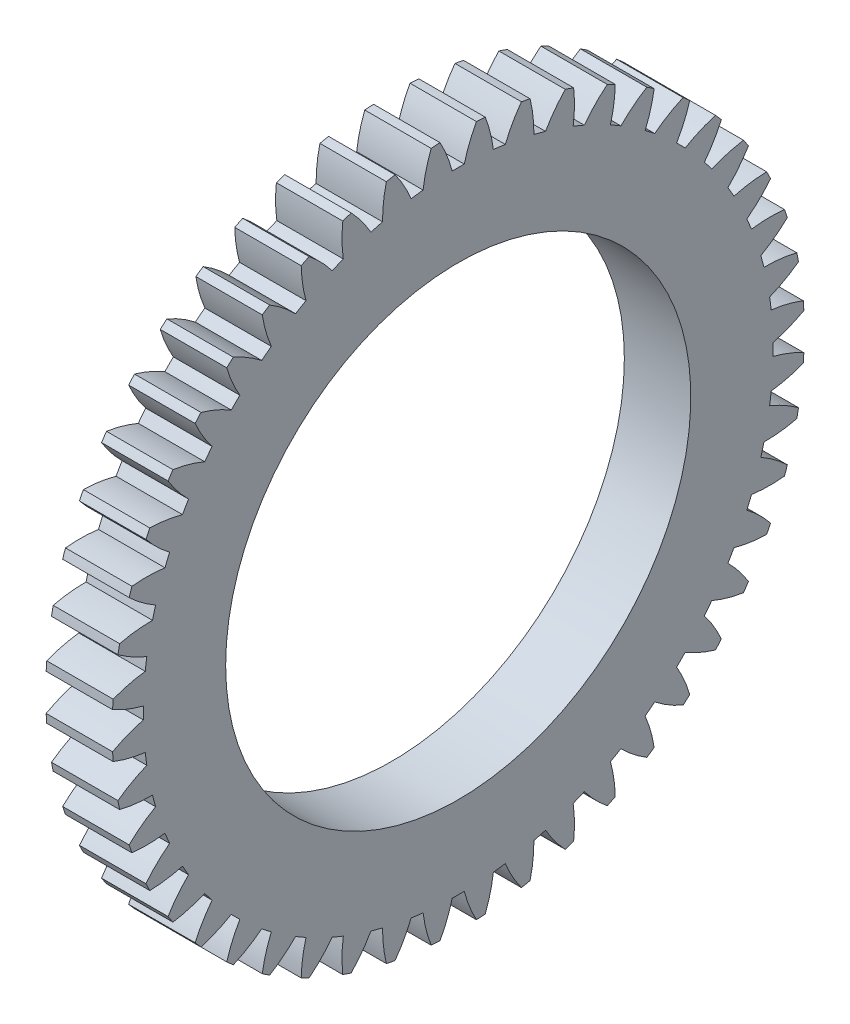
SolidWorks part; units mm, degrees
ref_plane "Plane1" through (0, 0, 0) normal (0, 0, 1) x (1, 0, 0)
ref_plane "Plane2" through (0, 0, 0) normal (0, 1, 0) x (1, 0, 0)
ref_plane "Plane3" through (0, 0, 0) normal (1, 0, 0) x (0, 0, -1)
other "Configuration Table"
sketch "HoldingSke" plane through (0, 0, 0) normal (0, 1, 0) x (1, 0, 0)
  line L0 (0, 0) -> (0.5353, -0.5945)
  line L1 (-15, 0) -> (100, 0) construction
  line L2 (0, 0) -> (-2.1039, 2.3779)
  line L3 (0, 0) -> (-11.863, 4.5341)
  line L4 (0, 0) -> (5.7786, 6.4178)
  line L5 (0, 0) -> (-46.8476, -17.4728)
  line L6 (0, 0) -> (-4.9738, -3.3558)
  line L7 (-2.1039, 2.3779) -> (8.6586, 51.2059)
  line L8 (-76.2, 54.61) -> (-72.9, 54.61)
  line L9 (-71.009, 38.7566) -> (-53.1078, 45.2721)
  line L10 (-76.2, 71.12) -> (104.1128, 71.12)
  line L11 (0, 0) -> (-6, 0)
  line L12 (-76.2, 101.6) -> (-76.155, 101.6)
  line L13 (24.9733, 27.94) -> (52.9518, 28.4284)
  line L14 (24.9733, 27.94) -> (24.9743, 27.94)
  line L15 (24.9733, 27.94) -> (100.4006, 29.5858)
  line L16 (-63.627, -1.25) -> (-12.827, -1.25)
  circle A0 centre (0, 0) radius 21
  circle A1 centre (0, 0) radius 28.4365
  circle A2 centre (0, 0) radius 37.5
  circle A3 centre (0, 0) radius 21
  dimension "MHD" = 56.873
  dimension "Hub_dia" = 75
  dimension "Bore" = 42
  dimension "MBD" = 42
  dimension "Num_teeth" = 48
  dimension "Pitch" = 0.8
  dimension "Overall_len" = 50
  dimension "Show_teeth" = 48
  dimension "Thickness" = 6
  dimension "OAL" = 50.0001
  dimension "T_dim" = 3.3
  dimension "Ap" = 20
  dimension "H" = 19.05
  dimension "Pitch_radius" = 180.3128
  dimension "Width" = 6
  dimension "Backlash" = 0.045
  dimension "Addendum_fac" = 1
  dimension "Dedendum_fac" = 1.25
  dimension "Clearance_fac" = 0.25
  dimension "Dedendum_add" = 0.001
  dimension "Module" = 1.25
sketch "BasProSke" plane through (0, 0, 0) normal (0, 1, 0) x (1, 0, 0)
  line L0 (-10, 0) -> (60, 0) construction
  line L1 (0, 0) -> (0, 31.25)
  line L2 (0, 0) -> (6, 0)
  line L3 (6, 0) -> (6, 31.25)
  line L4 (6, 31.25) -> (0, 31.25)
  dimension "Thickness" = 6
  dimension "Diameter" = 62.5
revolve "Base-Revolve" add sketch "BasProSke" angle 360 about L0
sketch "TooCutSke" plane through (0, 0, 0) normal (1, 0, 0) x (0, 0, -1)
  line L1 (0, 0) -> (0, 107) construction
  line L2 (0, 0) -> (-1.0603, 29.9813) construction
  line L3 (0, 0) -> (-3.9224, 59.8444) construction
  line L4 (-1.0603, 29.9813) -> (-1.9612, 29.9222) construction
  arc A0 (0.5453, 28.4313) -> (-0.5453, 28.4313) centre (0, 0) ccw
  arc A1 (1.6591, 31.2314) -> (-1.6591, 31.2314) centre (0, 0) ccw
  circle A2 centre (0, 0) radius 30 construction
  circle A3 centre (0, 0) radius 28.1908 construction
  arc A4 (-0.5453, 28.4313) -> (-1.6591, 31.2314) centre (-12.1643, 25.4313) ccw
  arc A5 (1.6591, 31.2314) -> (0.5453, 28.4313) centre (12.1643, 25.4313) ccw
  dimension "Root_dia" = 56.873
  dimension "Overcut_dia" = 62.5508
  dimension "Pitch_dia" = 60
  dimension "Base_dia" = 56.3816
  dimension "Flank_rad" = 12
  dimension "Half_ang" = 3.75
  dimension "Half_CT" = 0.9028
extrude "ToothCut" cut sketch "TooCutSke" along normal through all
fillet "Breaks" [suppressed] radius 0.025
fillet "RootFillets" [suppressed] radius 0.3135
pattern_circular "TeethCuts" count 48 every 7.5 about axis through (-10, 0, 0) along (1, 0, 0) of "ToothCut", "RootFillets", "Breaks"
sketch "HubNeaOneSke" plane through (0, 0, 0) normal (-1, 0, 0) x (0, 0, 1)
  circle A0 centre (0, 0) radius 28.4365
  dimension "Diameter" = 56.873
extrude "HubNearOne" [suppressed] add sketch "HubNeaOneSke" along normal blind 44.0001
sketch "HubNeaBotSke" plane through (0, 0, 0) normal (-1, 0, 0) x (0, 0, 1)
  circle A0 centre (0, 0) radius 28.4365
  dimension "Diameter" = 56.873
extrude "HubNearBoth" [suppressed] add sketch "HubNeaBotSke" along normal blind 22
ref_plane "FarPln" through (6, 0, 0) normal (1, 0, 0) x (0, 0, -1)
sketch "HubFarSke" plane through (6, 0, 0) normal (1, 0, 0) x (0, 0, -1)
  circle A0 centre (0, 0) radius 28.4365
  dimension "Diameter" = 56.873
extrude "HubFar" [suppressed] add sketch "HubFarSke" along normal blind 22
sketch "BorSke" plane through (0, 0, 0) normal (1, 0, 0) x (0, 0, -1)
  circle A0 centre (0, 0) radius 21
  dimension "Diameter" = 42
extrude "Bore" cut sketch "BorSke" along normal mid plane 100.0001
sketch "KeySke" plane through (0, 0, 0) normal (1, 0, 0) x (0, 0, -1)
  line L0 (-6, 0) -> (-6, 24.3)
  line L1 (-6, 24.3) -> (6, 24.3)
  line L2 (6, 24.3) -> (6, 0)
  line L3 (0, 0) -> (0, 34) construction
  line L4 (-6, 0) -> (6, 0)
  dimension "Offset" = 24.3
  dimension "Width" = 12
extrude "Keyway" [suppressed] cut sketch "KeySke" along normal mid plane 100.0001
pattern_circular "Keyway2" [suppressed] count 2 every 90 about axis through (-10, 0, 0) along (1, 0, 0)
sketch "Sketch1" plane through (6, 0, 0) normal (1, 0, 0) x (0, 0, -1)
  circle A0 centre (0, 0) radius 29.63
  dimension "D1" = 59.26
equation "' \"Module@HoldingSke\" = 6.35"
equation "' \"Num_teeth@HoldingSke\" = 12"
equation "' \"Ap@HoldingSke\" =  20"
equation "' \"Ap@HoldingSke\" = 20"
equation "' \"Width@HoldingSke\" = 0.5 * 25.4"
equation "' \"Hub_dia@HoldingSke\"= 1 * 25.4"
equation "' \"Hub_dia@HoldingSke\" = 1 * 25.4"
equation "' \"Overall_len@HoldingSke\" = 1.0 * 25.4"
equation "' \"Bore@HoldingSke\" = 0.75 * 25.4"
equation "' \"T_dim@HoldingSke\" = 0.1 * 25.4"
equation "' \"Width@KeySke\" = 0.25 * 25.4"
equation "' \"Show_teeth@HoldingSke\" = 13"
equation "' \"Backlash@HoldingSke\" = 0.009 * 25.4"
equation "' \"Addendum_fac@HoldingSke\" = 1.0"
equation "' \"Dedendum_fac@HoldingSke\" = 1.25"
equation "' \"Dedendum_add@HoldingSke\" = 0.00005 * 25.4"
equation "' \"Clearance_fac@HoldingSke\" = 0.25"
equation "\"Pitch@HoldingSke\" = 1 / \"Module@HoldingSke\""
equation "\"Overcut_dia@TooCutSke\" = (\"Num_teeth@HoldingSke\" + 2 * \"Addendum_fac@HoldingSke\") / \"Pitch@HoldingSke\" + 0.002 * 25.4"
equation "\"Pitch_dia@TooCutSke\" = \"Num_teeth@HoldingSke\" / \"Pitch@HoldingSke\""
equation "\"Base_dia@TooCutSke\" = \"Num_teeth@HoldingSke\" / \"Pitch@HoldingSke\" * cos((\"Ap@HoldingSke\"  * 3.14159265 / 180))"
equation "\"Root_dia@TooCutSke\" = (\"Num_teeth@HoldingSke\" + 2) / \"Pitch@HoldingSke\" - 2 * (\"Addendum_fac@HoldingSke\" + \"Dedendum_fac@HoldingSke\") / \"Pitch@HoldingSke\" - \"Dedendum_add@HoldingSke\" * 2"
equation "\"Half_ang@TooCutSke\" = 180 / \"Num_teeth@HoldingSke\""
equation "\"Half_CT@TooCutSke\" = \"Num_teeth@HoldingSke\" / \"Pitch@HoldingSke\" * sin((3.14159265 / 2 / \"Num_teeth@HoldingSke\")) / 2 - 7 * \"Backlash@HoldingSke\" / 4"
equation "\"Flank_rad@TooCutSke\" = \"Num_teeth@HoldingSke\" / \"Pitch@HoldingSke\" / 5"
equation "\"Radius@RootFillets\" = \"Clearance_fac@HoldingSke\" / \"Pitch@HoldingSke\" + \"Dedendum_add@HoldingSke\""
equation "\"Break_rad@Breaks\" = 0.02 / \"Pitch@HoldingSke\""
equation "\"Thickness@HoldingSke\" = \"Width@HoldingSke\""
equation "\"OAL@HoldingSke\" = \"Thickness@HoldingSke\""
equation "\"MHD@HoldingSke\" = (\"Num_teeth@HoldingSke\" + 2) / \"Pitch@HoldingSke\" - 2 * (\"Addendum_fac@HoldingSke\" + \"Dedendum_fac@HoldingSke\")  / \"Pitch@HoldingSke\" - \"Dedendum_add@HoldingSke\" * 2"
equation "\"MBD@HoldingSke\" = (\"Num_teeth@HoldingSke\" + 2) / \"Pitch@HoldingSke\" - 2 * (\"Addendum_fac@HoldingSke\" + \"Dedendum_fac@HoldingSke\")  / \"Pitch@HoldingSke\" - \"Dedendum_add@HoldingSke\" * 2 - 0.002 * 25.4"
equation "\"MHD@HoldingSke\" = ((sgn( \"MHD@HoldingSke\" - \"Hub_dia@HoldingSke\" )-1)*( \"MHD@HoldingSke\" - \"Hub_dia@HoldingSke\" ))/-2+ \"Hub_dia@HoldingSke\""
equation "\"MBD@HoldingSke\" = ((sgn( \"MBD@HoldingSke\" - \"Bore@HoldingSke\" )-1)*( \"MBD@HoldingSke\" - \"Bore@HoldingSke\" ))/-2+ \"Bore@HoldingSke\""
equation "\"OAL@HoldingSke\" = ((sgn( \"OAL@HoldingSke\" - \"Overall_len@HoldingSke\" )+1)*( \"OAL@HoldingSke\" - \"Overall_len@HoldingSke\" ))/2 + \"Overall_len@HoldingSke\" + 0.000002 * 25.4"
equation "\"Num_teeth@TeethCuts\" = int( \"Show_teeth@HoldingSke\" ) + 1"
equation "\"Num_teeth@TeethCuts\" = ((sgn( \"Num_teeth@TeethCuts\" - \"Num_teeth@HoldingSke\" )-1)*( \"Num_teeth@TeethCuts\" - \"Num_teeth@HoldingSke\" ))/-2+ \"Num_teeth@HoldingSke\""
equation "\"Num_teeth@TeethCuts\" = ((sgn( \"Num_teeth@TeethCuts\" - 2.0)+1)*( \"Num_teeth@TeethCuts\" - 2.0))/2 +2.0"
equation "\"Angle@TeethCuts\" = 360.0 / \"Num_teeth@HoldingSke\""
equation "\"Diameter@BasProSke\" = (\"Num_teeth@HoldingSke\" + 2 * \"Addendum_fac@HoldingSke\") / \"Pitch@HoldingSke\""
equation "\"Thickness@BasProSke\"  = \"Thickness@HoldingSke\""
equation "' \"Fillet_rad@BasProSke\" =  \"Thickness@HoldingSke\" * 0.05"
equation "' \"Fillet_rad@BasProSke\" = \"Thickness@HoldingSke\" * 0.05"
equation "\"MHD@HoldingSke\" = ((sgn( \"MHD@HoldingSke\" - \"Root_dia@TooCutSke\" )-1)*( \"MHD@HoldingSke\" - \"Root_dia@TooCutSke\" ))/-2+ \"Root_dia@TooCutSke\""
equation "\"Diameter@HubNeaOneSke\" = \"MHD@HoldingSke\""
equation "\"Length@HubNearOne\" = \"OAL@HoldingSke\" - \"Thickness@BasProSke\""
equation "\"Diameter@HubNeaBotSke\" = \"MHD@HoldingSke\""
equation "\"Length@HubNearBoth\" = ( \"OAL@HoldingSke\" - \"Thickness@BasProSke\" ) / 2.0"
equation "\"Thickness@FarPln\" = \"Thickness@BasProSke\""
equation "\"Diameter@HubFarSke\" = \"MHD@HoldingSke\""
equation "\"Length@HubFar\" = ( \"OAL@HoldingSke\" - \"Thickness@BasProSke\" ) / 2.0"
equation "\"Diameter@BorSke\" = \"MBD@HoldingSke\""
equation "\"D1@Bore\" = \"OAL@HoldingSke\" * 2.0"
equation "\"D1@Keyway\" = \"OAL@HoldingSke\" * 2.0"
equation "\"Offset@KeySke\" = \"T_dim@HoldingSke\" + \"MBD@HoldingSke\" / 2.0"
